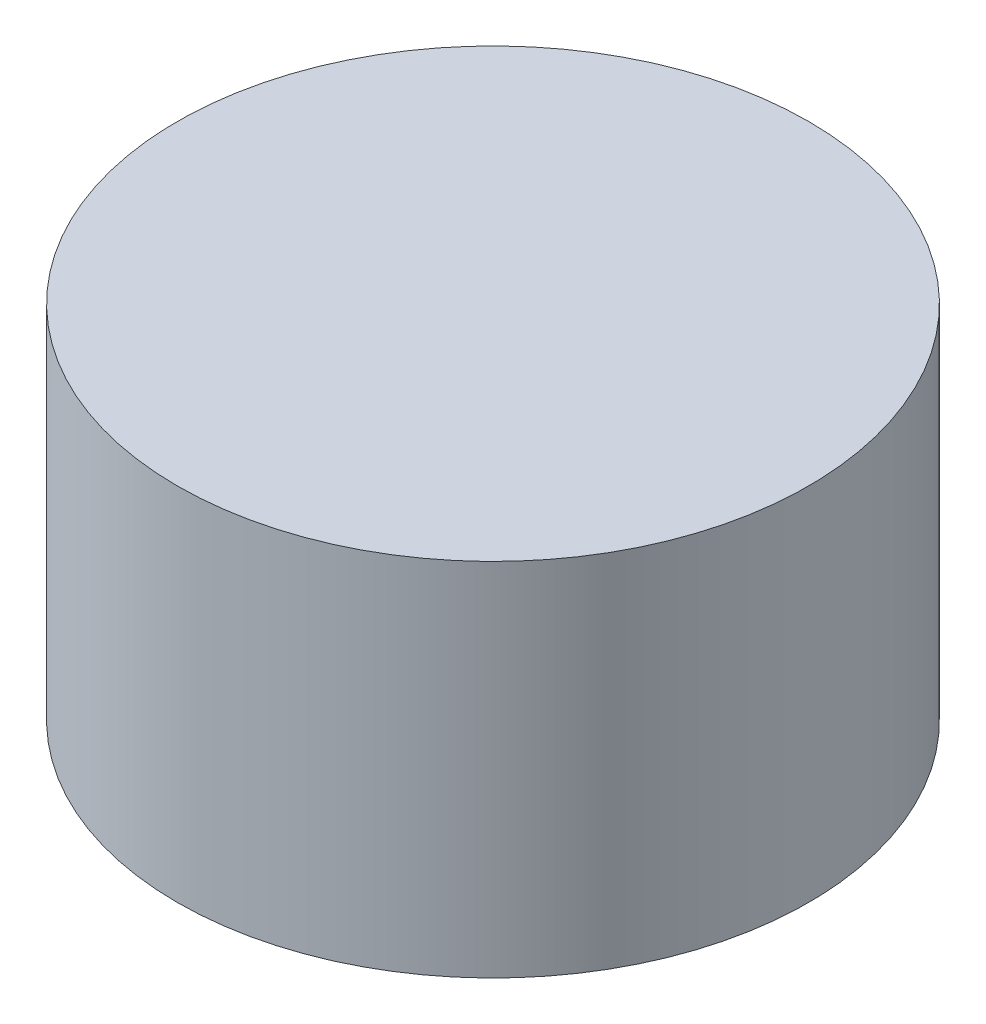
SolidWorks part; units mm, degrees
ref_plane "Front Plane" through (0, 0, 0) normal (0, 0, 1) x (1, 0, 0)
ref_plane "Top Plane" through (0, 0, 0) normal (0, 1, 0) x (1, 0, 0)
ref_plane "Right Plane" through (0, 0, 0) normal (1, 0, 0) x (0, 0, -1)
sketch "Sketch1" plane through (0, 0, 0) normal (0, 1, 0) x (1, 0, 0)
  circle A0 centre (0, 0) radius 21
extrude "Boss-Extrude1" add sketch "Sketch1" along normal blind 24
